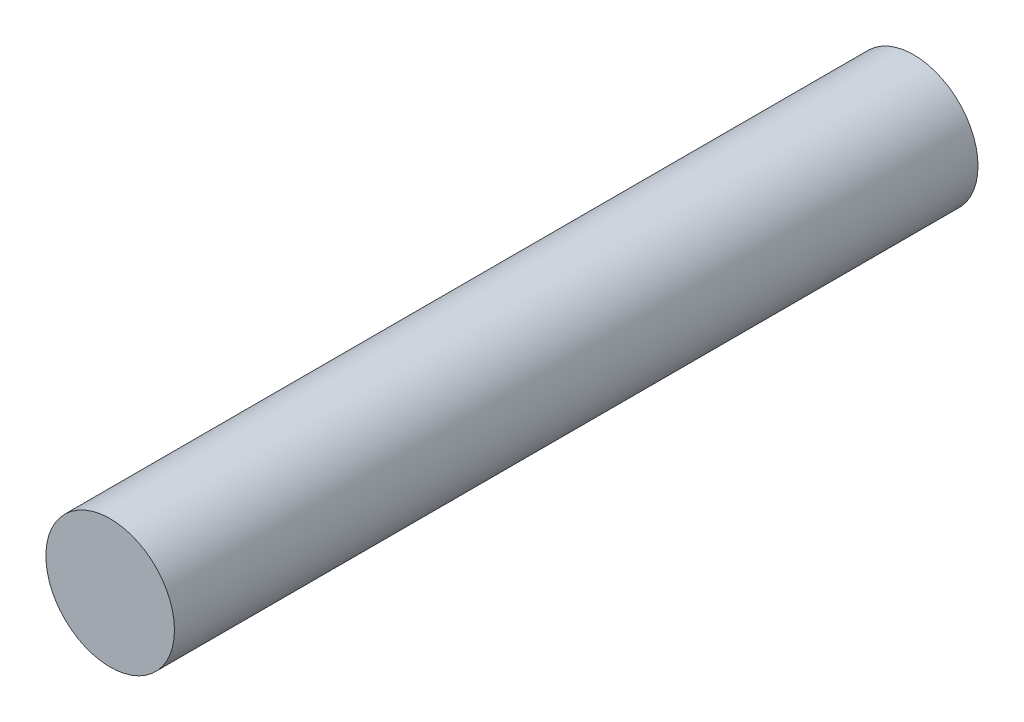
SolidWorks part; units mm, degrees
ref_plane "Plan de face" through (0, 0, 0) normal (0, 0, 1) x (1, 0, 0)
ref_plane "Plan de dessus" through (0, 0, 0) normal (0, 1, 0) x (1, 0, 0)
ref_plane "Plan de droite" through (0, 0, 0) normal (1, 0, 0) x (0, 0, -1)
sketch "Esquisse2" plane through (0, 0, 0) normal (0, 0, 1) x (1, 0, 0)
  circle A0 centre (0, 0) radius 2.032
  dimension "D1" = 4.064
extrude "Boss.-Extru.1" add sketch "Esquisse2" along normal mid plane 25.4
